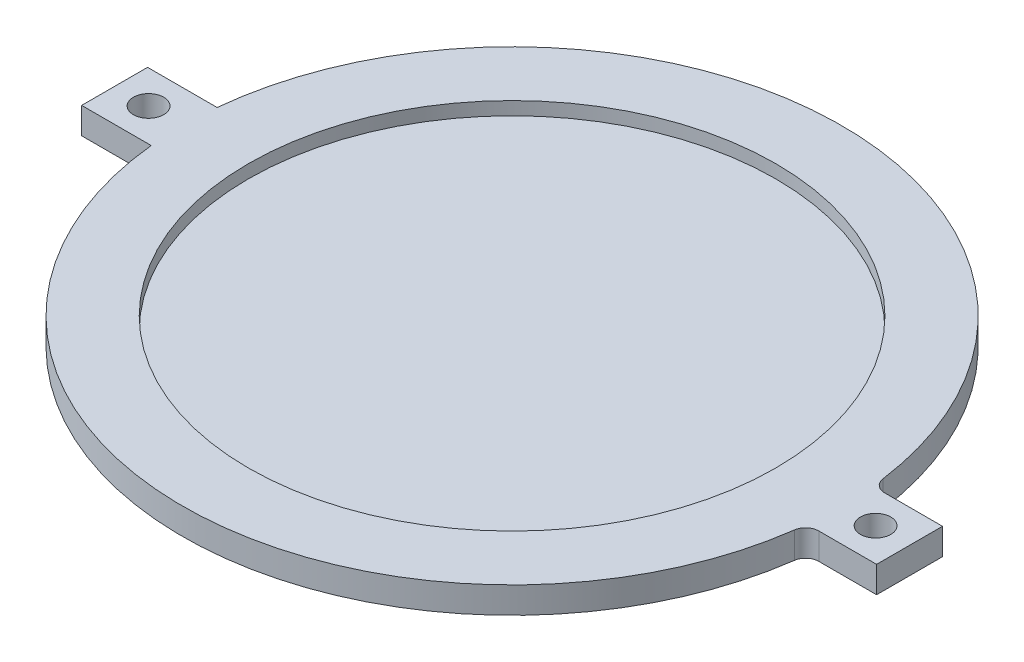
SolidWorks part; units mm, degrees
material "POLIURETANO (11671)"
ref_plane "Alzado" through (0, 0, 0) normal (0, 0, 1) x (1, 0, 0)
ref_plane "Planta" through (0, 0, 0) normal (0, 1, 0) x (1, 0, 0)
ref_plane "Vista lateral" through (0, 0, 0) normal (1, 0, 0) x (0, 0, -1)
sketch "Croquis1" plane through (0, 0, 0) normal (0, 1, 0) x (1, 0, 0)
  line L0 (25, 0) -> (30.15, 0) construction
  line L1 (19.85, -2.5) -> (30.15, -2.5)
  line L2 (19.85, -2.5) -> (19.85, 2.5)
  line L3 (19.85, 2.5) -> (30.15, 2.5)
  line L4 (30.15, -2.5) -> (30.15, 2.5)
  line L5 (19.85, -2.5) -> (30.15, 2.5) construction
  line L6 (19.85, 2.5) -> (30.15, -2.5) construction
  line L7 (0, 25) -> (0, -25) construction
  line L8 (-19.85, 2.5) -> (-30.15, 2.5)
  line L9 (-30.15, -2.5) -> (-30.15, 2.5)
  line L10 (-19.85, -2.5) -> (-30.15, -2.5)
  line L11 (-19.85, -2.5) -> (-19.85, 2.5)
  circle A0 centre (0, 0) radius 25
  circle A1 centre (27.575, 0) radius 1.15
  circle A2 centre (-27.575, 0) radius 1.15
  point P3 (25, 0)
  dimension "D1" = 50
  dimension "D4" = 2.3
  dimension "D2" = 5
  dimension "D3" = 5.15
extrude "Saliente-Extruir1" add sketch "Croquis1" along normal blind 2 contours L3 A0 L1 L2 | L1 A0 L3 L2 | A0 L1 L4 L3 A1 | A0 L8 L9 L10 A2 | L8 A0 L10 L11
fillet "Redondeo1" radius 1 2 edges at (24.8747, 1, -2.5) (24.8747, 1, 2.5)
sketch "Croquis2" plane through (0, 2, 0) normal (0, 1, 0) x (1, 0, 0)
  circle A0 centre (0, 0) radius 20
  dimension "D1" = 40
extrude "Cortar-Extruir1" cut sketch "Croquis2" against normal blind 1
